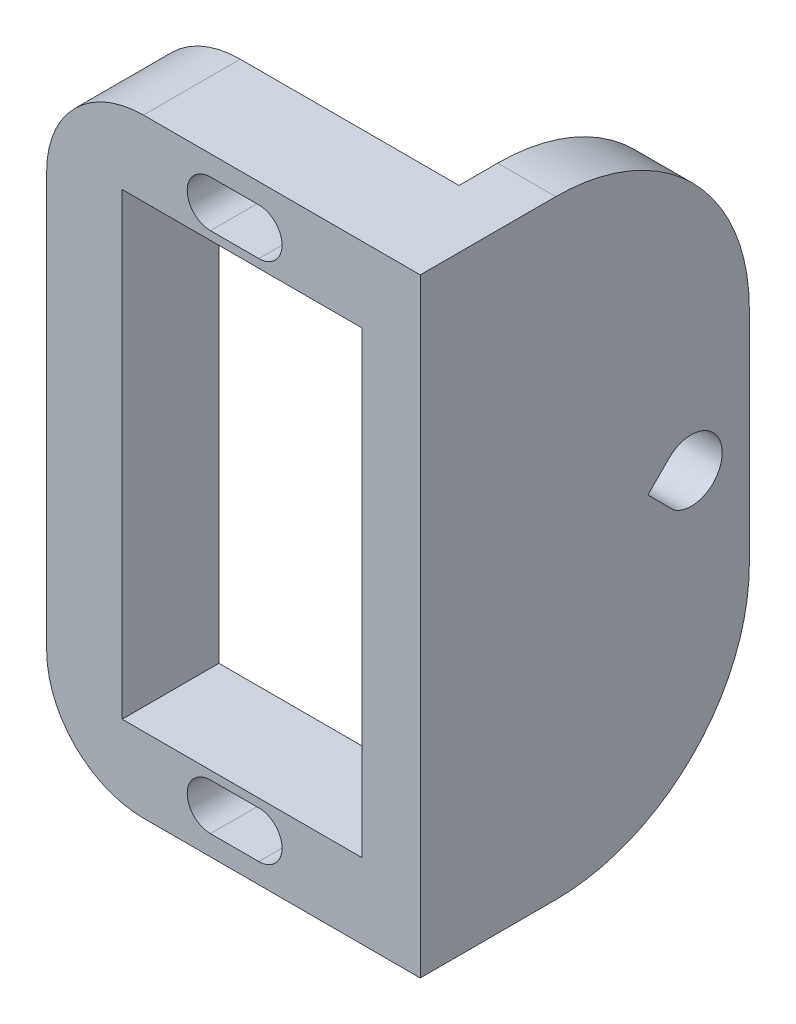
SolidWorks part; units mm, degrees
ref_plane "Front Plane" through (0, 0, 0) normal (1, 0, 0) x (0, 1, 0)
ref_plane "Top Plane" through (0, 0, 0) normal (0, 0, 1) x (0, 1, 0)
ref_plane "Right Plane" through (0, 0, 0) normal (0, 1, 0) x (-1, 0, 0)
sketch "Sketch1" plane through (0, 0, 0) normal (0, 0, 1) x (0, 1, 0)
  line L0 (-11.85, 0) -> (11.85, 0)
  line L5 (-11.85, 0) -> (-11.85, -12.4)
  line L7 (-11.85, 0) -> (-11.85, -5.81) construction
  line L8 (-15.73, 3.9) -> (15.73, 3.9)
  line L11 (-15.73, -12.4) -> (-15.73, -0.1)
  line L12 (-15.73, -0.1) -> (-15.73, 3.9)
  line L14 (-15.73, -15.4) -> (-11.85, -15.4)
  line L15 (11.85, 0) -> (11.85, -5.81) construction
  line L16 (15.73, -0.1) -> (15.73, 3.9)
  line L17 (15.73, -12.4) -> (15.73, -0.1)
  line L19 (11.85, 0) -> (11.85, -12.4)
  line L21 (0, 0) -> (0, -16.7663) construction
  line L23 (15.73, -15.4) -> (11.85, -15.4)
  line L27 (-11.85, -12.4) -> (-11.85, -15.4)
  line L28 (11.85, -12.4) -> (11.85, -15.4)
  line L29 (-15.73, -12.4) -> (-15.73, -15.4)
  line L30 (15.73, -12.4) -> (15.73, -15.4)
  circle A0 centre (-13.49, -5.81) radius 1.2 construction
  circle A1 centre (13.49, -5.81) radius 1.2 construction
  point P3 (0, 0)
  dimension "D3" = 12.3
  dimension "D5" = 2.4
  dimension "D1" = 3.88
  dimension "D2" = 23.7
  dimension "D4" = 12.4
  dimension "D6" = 4
  dimension "D7" = 31.46
  dimension "D8" = 3
  dimension "D9" = 4
  dimension "D10" = 12.3
  dimension "D11" = 3
  dimension "D12" = 3.88
extrude "Boss-Extrude2" add sketch "Sketch1" along normal blind 5
sketch "Sketch2" plane through (0, 0, 5) normal (0, 0, 1) x (1, 0, 0)
  line L0 (4.56, -13.49) -> (7.06, -13.49) construction
  line L1 (4.56, -12.29) -> (7.06, -12.29)
  line L2 (4.56, -14.69) -> (7.06, -14.69)
  line L3 (0, 0) -> (15.8756, 0) construction
  line L4 (0, -11.85) -> (0, 11.85) construction
  line L5 (4.56, 13.49) -> (7.06, 13.49) construction
  line L6 (4.56, 12.29) -> (7.06, 12.29)
  line L7 (4.56, 14.69) -> (7.06, 14.69)
  arc A2 (4.56, -12.29) -> (4.56, -14.69) centre (4.56, -13.49) ccw
  arc A3 (7.06, -14.69) -> (7.06, -12.29) centre (7.06, -13.49) ccw
  arc A4 (4.56, 12.29) -> (4.56, 14.69) centre (4.56, 13.49) cw
  arc A5 (7.06, 14.69) -> (7.06, 12.29) centre (7.06, 13.49) cw
  point P8 (5.81, -13.49)
  point P20 (5.81, 13.49)
  dimension "D1" = 2.5
  dimension "D2" = 1.2
extrude "Cut-Extrude1" cut sketch "Sketch2" against normal through all
sketch "Sketch3" plane through (0, 0, 0) normal (0, 0, -1) x (1, 0, 0)
  line L0 (15.4, 11.85) -> (0, 11.85) construction
  line L1 (15.4, 15.73) -> (12.4, 15.73)
  line L2 (15.4, 15.73) -> (15.4, 11.85)
  line L3 (15.4, 11.85) -> (12.4, 11.85)
  line L4 (12.4, 15.73) -> (12.4, 11.85)
  line L5 (0, -11.85) -> (15.4, -11.85) construction
  line L6 (15.4, -15.73) -> (12.4, -15.73)
  line L7 (15.4, -15.73) -> (15.4, -11.85)
  line L8 (15.4, -11.85) -> (12.4, -11.85)
  line L9 (12.4, -15.73) -> (12.4, -11.85)
  line M3 (15.4, -11.85) -> (0, -11.85)
  line M9 (-3.9, -15.73) -> (15.4, -15.73)
  line M10 (15.4, -15.73) -> (15.4, -11.85)
  dimension "D1" = 3
  dimension "D2" = 3
extrude "Boss-Extrude3" add sketch "Sketch3" along normal blind 12 contours L9 M9 M10 M3 | L4 L3 L2 L1
sketch "Sketch4" plane through (0, -11.85, 0) normal (0, 1, 0) x (-1, 0, 0)
  line L0 (-12.4, -12) -> (-12.4, 0) construction
  line L1 (-15.4, -12) -> (-12.4, -12)
  line L2 (-15.4, -12) -> (-15.4, -5.9215)
  line L3 (-15.4, -5.9215) -> (-12.4, -5.9215)
  line L4 (-12.4, -12) -> (-12.4, -5.9215)
extrude "Boss-Extrude4" add sketch "Sketch4" along normal up to next
sketch "Sketch6" plane through (0, 0, -5.9215) normal (0, 0, 1) x (1, 0, 0)
  line L1 (12.4, 11.85) -> (15.4, 11.85)
  line L2 (12.4, 11.85) -> (12.4, -11.85)
  line L3 (12.4, -11.85) -> (15.4, -11.85)
  line L4 (15.4, 11.85) -> (15.4, -11.85)
extrude "Boss-Extrude5" add sketch "Sketch6" along normal up to vertex (10.9215 mm away)
sketch "Sketch5" plane through (12.4, 0, 0) normal (-1, 0, 0) x (0, -1, 0)
  line L0 (0, -12) -> (0, 0) construction
  line L1 (-15.73, -12) -> (15.73, -12) construction
  line L2 (0, -6.7596) -> (-1.109, -7.8686)
  line L4 (0, -6.7596) -> (1.3553, -8.1149)
  line L5 (-15.6853, -9) -> (15.73, -9) construction
  line L6 (15.73, -12) -> (15.73, 0) construction
  arc A0 (-1.109, -7.8686) -> (1.3553, -8.1149) centre (0.0224, -9) ccw
  dimension "D1" = 3.2
  dimension "D2" = 3
  dimension "D3" = 45
  dimension "D4" = 45
extrude "Cut-Extrude2" cut sketch "Sketch5" against normal through all
fillet "Fillet1" radius 10 2 edges at (13.9, -15.73, -12) (13.9, 15.73, -12)
fillet "Fillet2" radius 5 2 edges at (-3.9, -15.73, 2.5) (-3.9, 15.73, 2.5)
